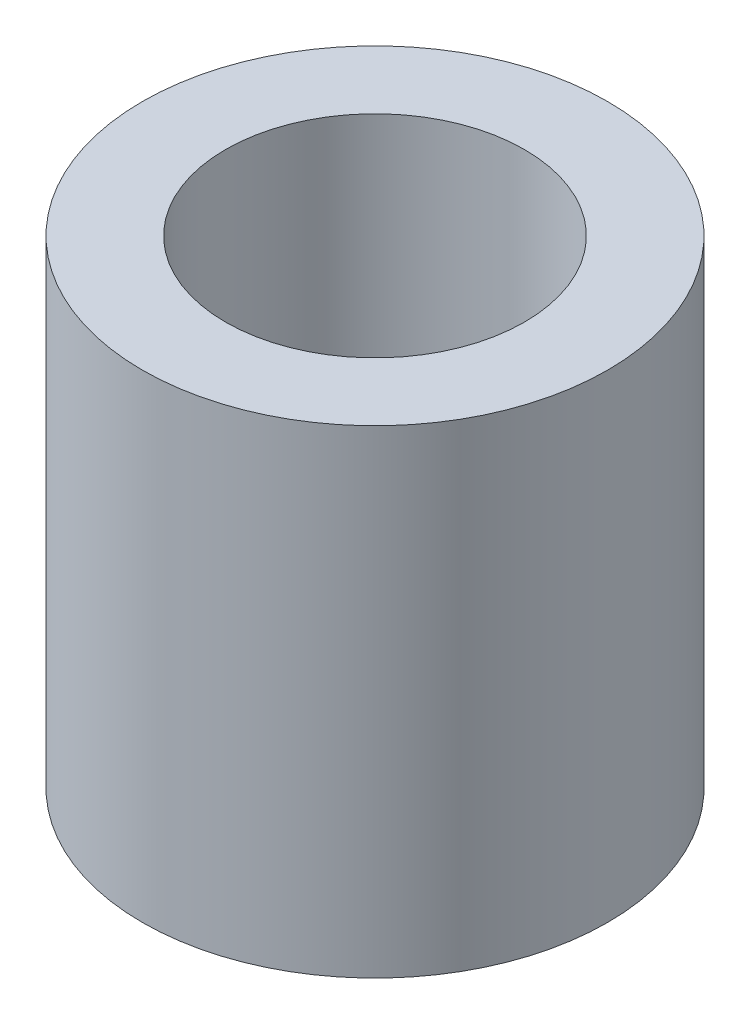
SolidWorks part; units mm, degrees
ref_plane "Front Plane" through (0, 0, 0) normal (0, 0, 1) x (1, 0, 0)
ref_plane "Top Plane" through (0, 0, 0) normal (0, 1, 0) x (1, 0, 0)
ref_plane "Right Plane" through (0, 0, 0) normal (1, 0, 0) x (0, 0, -1)
sketch "Sketch2" plane through (0, 0, 0) normal (0, 1, 0) x (1, 0, 0)
  circle A0 centre (0, 0) radius 1.5875
  circle A1 centre (0, 0) radius 2.4704
  dimension "D1" = 3.175
extrude "Boss-Extrude1" add sketch "Sketch2" along normal blind 5.08
